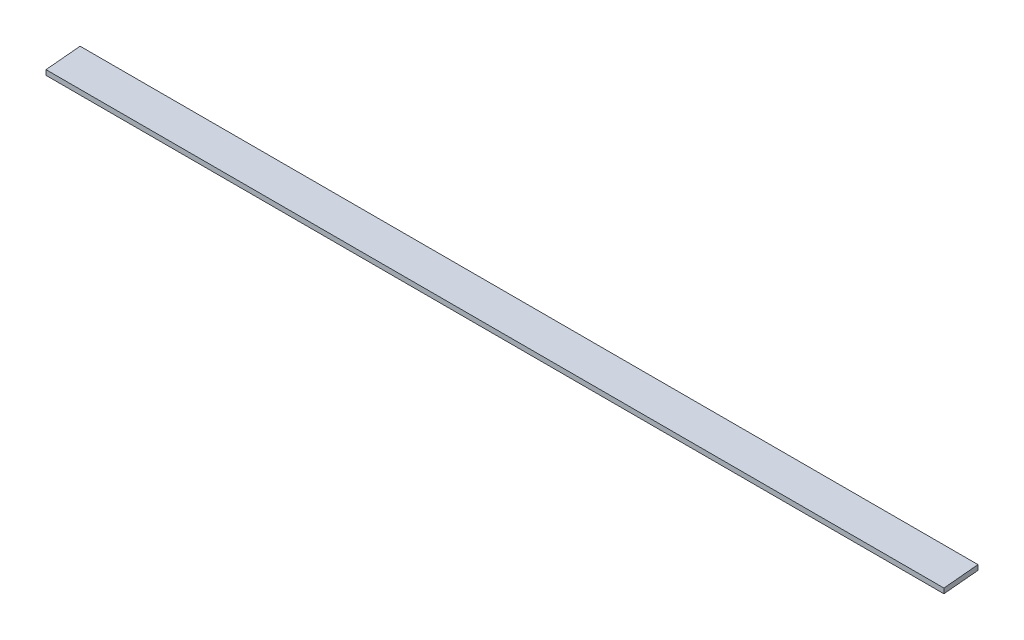
SolidWorks part; units mm, degrees
ref_plane "Front Plane" through (0, 0, 0) normal (0, 0, 1) x (1, 0, 0)
ref_plane "Top Plane" through (0, 0, 0) normal (0, 1, 0) x (1, 0, 0)
ref_plane "Right Plane" through (0, 0, 0) normal (1, 0, 0) x (0, 0, -1)
sketch "Sketch1" plane through (0, 0, 0) normal (0, 1, 0) x (1, 0, 0)
  line L1 (-1143, -44.45) -> (1143, -44.45)
  line L2 (-1143, -44.45) -> (-1143, 44.45)
  line L3 (-1143, 44.45) -> (1143, 44.45)
  line L4 (1143, -44.45) -> (1143, 44.45)
  line L5 (-1143, -44.45) -> (1143, 44.45) construction
  line L6 (-1143, 44.45) -> (1143, -44.45) construction
  point P0 (0, 0)
  dimension "D1" = 88.9
  dimension "D2" = 2286
extrude "Boss-Extrude1" add sketch "Sketch1" along normal blind 11.9062
hole_wizard "1/4 Clearance Hole1" positions "Sketch2" profile "Sketch3" hole size "1/4" standard "ANSI Inch"
sketch "Sketch2" plane through (0, 11.9062, 0) normal (0, 1, 0) x (1, 0, 0)
  line L0 (-1143, -44.45) -> (1143, -44.45) construction
  line L1 (1143, -44.45) -> (1143, 44.45) construction
  point P0 (1041.4, 0)
  point P8 (-931.9249, 0)
  point P10 (-952.6211, 23.8729)
  point P12 (-948.6978, -26.7753)
  point P14 (1058.1729, 26.7753)
  point P16 (1062.0962, -23.8729)
  dimension "D1" = 44.45
  dimension "D2" = 101.6
sketch "Sketch3" plane through (1041.4, 11.9062, 0) normal (1, 0, 0) x (0, 0, 1)
  line L0 (0, 0) -> (0, 11.9062)
  line L1 (0, 11.9062) -> (3.3782, 11.9062)
  line L2 (3.3782, 11.9062) -> (3.3782, 0)
  line L5 (3.3782, 0) -> (0, 0)
  line L11 (0, -6.35) -> (0, 107.95) construction
  dimension "Thru Hole Dia." = 6.7564
  dimension "Thru Hole Depth" = 11.9062
sketch "Sketch4" plane through (0, 0, 0) normal (0, -1, 0) x (1, 0, 0)
  line L0 (-1143, -44.45) -> (-1143, 44.45)
  line L1 (-1143, -44.45) -> (-1143, 44.45) construction
  line L2 (1143, -44.45) -> (-1143, -44.45) construction
  line L3 (-1143, 44.45) -> (1143, 44.45) construction
  line L4 (-1017.4277, -44.45) -> (-1009.65, 44.45)
  line L5 (-1009.65, 44.45) -> (-1143, 44.45)
  line L6 (-1017.4277, -44.45) -> (-1143, -44.45)
  line L7 (1120.141, -44.45) -> (1127.9187, 44.45)
  line L8 (1127.9187, 44.45) -> (1143, 44.45)
  line L9 (1143, 44.45) -> (1143, -44.45)
  line L10 (1143, -44.45) -> (1120.141, -44.45)
  line L11 (1143, 44.45) -> (1143, -44.45) construction
  line L12 (-1143, 44.45) -> (1143, 44.45) construction
  dimension "D1" = 85
  dimension "D2" = 85
  dimension "D3" = 133.35
  dimension "D4" = 15.0812
extrude "Cut-Extrude1" cut sketch "Sketch4" against normal through all
